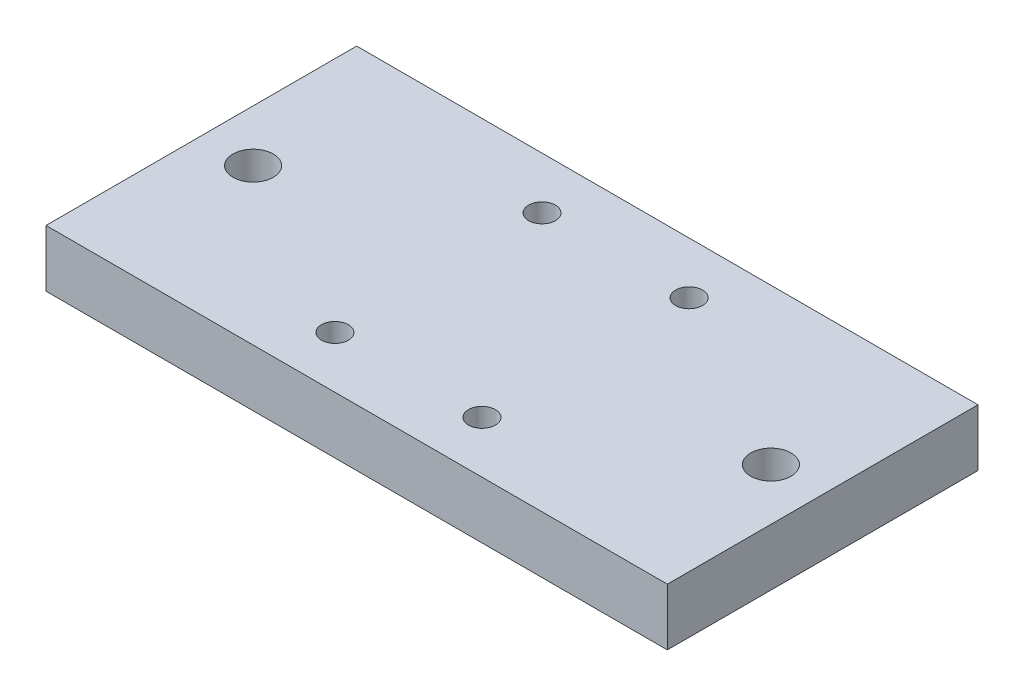
SolidWorks part; units mm, degrees
ref_plane "前视基准面" through (0, 0, 0) normal (0, 0, 1) x (1, 0, 0)
ref_plane "上视基准面" through (0, 0, 0) normal (0, 1, 0) x (1, 0, 0)
ref_plane "右视基准面" through (0, 0, 0) normal (1, 0, 0) x (0, 0, -1)
sketch "草图1" plane through (0, 0, 0) normal (0, 1, 0) x (1, 0, 0)
  line L1 (0, 300) -> (600, 300)
  line L2 (0, 300) -> (0, 0)
  line L3 (0, 0) -> (600, 0)
  line L4 (600, 300) -> (600, 0)
  dimension "D1" = 600
  dimension "D2" = 300
extrude "凸台-拉伸1" add sketch "草图1" along normal blind 55
sketch "草图2" plane through (0, 55, 0) normal (0, 1, 0) x (1, 0, 0)
  line L0 (-1000, 150) -> (49000, 150) construction
  line L1 (0, 300) -> (0, 0) construction
  line L2 (50, -829.0666) -> (50, 49170.9334) construction
  line L3 (550, -810.5051) -> (550, 49189.4949) construction
  line L4 (600, 0) -> (600, 300) construction
  line L5 (300, -700) -> (300, 49300) construction
  line L6 (600, 300) -> (0, 300) construction
  line L7 (229, -809.4287) -> (229, 49190.5713) construction
  line L9 (371, -811.1019) -> (371, 49188.8981) construction
  line L10 (-677.258, 250) -> (49322.742, 250) construction
  line L11 (-658.0162, 50) -> (49341.9838, 50) construction
  circle A0 centre (50, 150) radius 19.5
  circle A1 centre (550, 150) radius 19.5
  circle A2 centre (371, 250) radius 13
  circle A3 centre (229, 250) radius 13
  circle A4 centre (371, 50) radius 13
  circle A5 centre (229, 50) radius 13
  point P5 (0, 150)
  point P20 (300, 300)
  dimension "D3" = 39
  dimension "D8" = 26
  dimension "D1" = 50
  dimension "D2" = 50
  dimension "D4" = 100
  dimension "D5" = 100
  dimension "D6" = 71
  dimension "D7" = 71
extrude "切除-拉伸1" cut sketch "草图2" against normal through all
